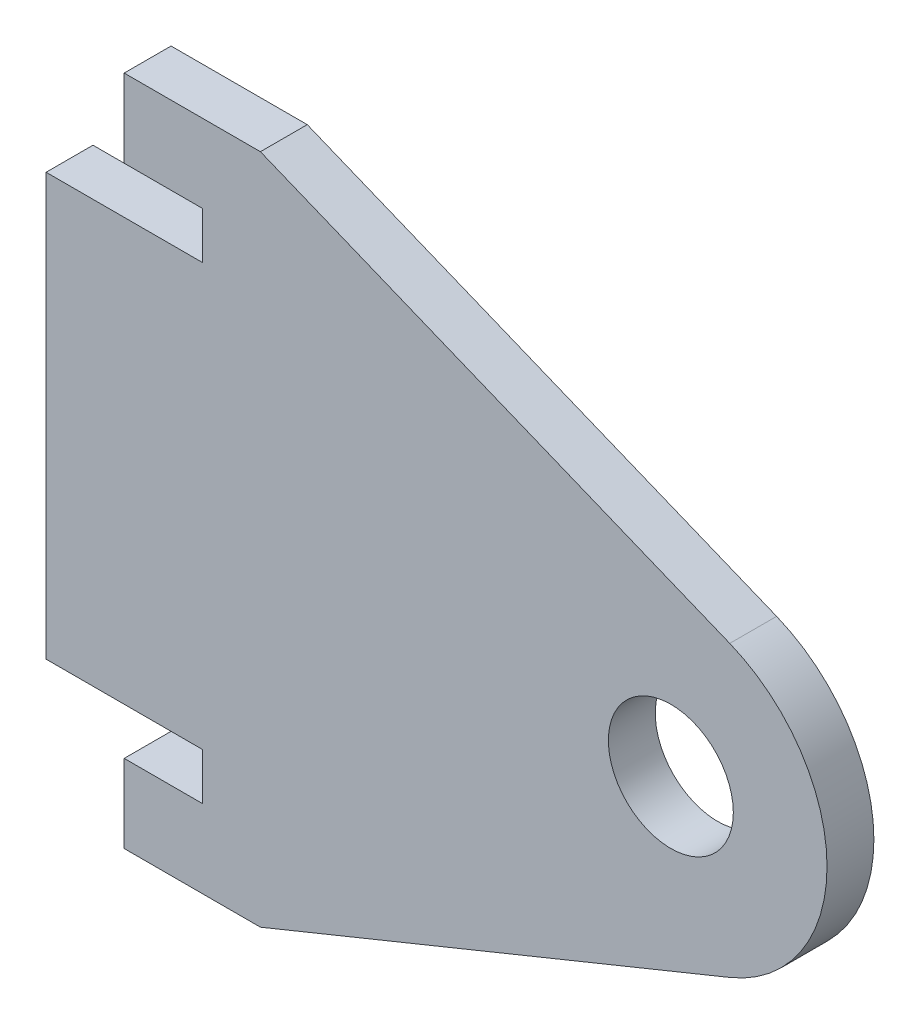
SolidWorks part; units mm, degrees
ref_plane "Plan de face" through (0, 0, 0) normal (0, 0, 1) x (1, 0, 0)
ref_plane "Plan de dessus" through (0, 0, 0) normal (0, 1, 0) x (1, 0, 0)
ref_plane "Plan de droite" through (0, 0, 0) normal (1, 0, 0) x (0, 0, -1)
sketch "Esquisse1" plane through (0, 0, 0) normal (0, 0, 1) x (1, 0, 0)
  line L0 (-11.6615, 23.4846) -> (-11.6615, -3.5154)
  line L1 (-11.6615, 31.4846) -> (2.0593, 31.4846)
  line L2 (-11.6615, 31.4846) -> (-11.6615, 26.4846)
  line L3 (-11.6615, -11.5154) -> (2.0593, -11.5154)
  line L5 (-11.6615, 26.4846) -> (-1.6615, 26.4846)
  line L7 (-11.6615, 23.4846) -> (-1.6615, 23.4846)
  line L8 (-1.6615, 26.4846) -> (-1.6615, 23.4846)
  line L9 (-11.6615, -3.5154) -> (-1.6615, -3.5154)
  line L11 (-11.6615, -6.5154) -> (-1.6615, -6.5154)
  line L12 (-1.6615, -3.5154) -> (-1.6615, -6.5154)
  line L13 (-11.6615, -6.5154) -> (-11.6615, -11.5154)
  line L14 (-11.6615, 9.9846) -> (28.3385, 9.9846) construction
  line L15 (2.0593, 31.4846) -> (32.1103, 19.246)
  line L16 (32.1103, 0.7232) -> (2.0593, -11.5154)
  circle A0 centre (28.3385, 9.9846) radius 4
  arc A1 (32.1103, 19.246) -> (32.1103, 0.7232) centre (28.3385, 9.9846) cw
  dimension "D6" = 8
  dimension "D7" = 10
  dimension "D1" = 3
  dimension "D2" = 3
  dimension "D3" = 33
  dimension "D4" = 5
  dimension "D5" = 5
  dimension "D8" = 10
  dimension "D9" = 10
  dimension "D10" = 40
extrude "Boss.-Extru.1" add sketch "Esquisse1" along normal blind 3
sketch "Esquisse2" plane through (0, 0, 3) normal (0, 0, 1) x (1, 0, 0)
  line L0 (-11.6615, 31.4846) -> (-11.6615, 26.4846) construction
  line L1 (-12.5217, 35.1219) -> (-6.6615, 35.1219)
  line L2 (-12.5217, 35.1219) -> (-12.5217, 25.0874)
  line L3 (-12.5217, 25.0874) -> (-6.6615, 25.0874)
  line L4 (-6.6615, 35.1219) -> (-6.6615, 25.0874)
  line L5 (-11.6615, 9.9846) -> (6.3373, 9.9846) construction
  line L6 (-11.6615, 23.4846) -> (-11.6615, -3.5154) construction
  line L7 (-12.5217, -5.1181) -> (-6.6615, -5.1181)
  line L8 (-6.6615, -15.1526) -> (-6.6615, -5.1181)
  line L9 (-12.5217, -15.1526) -> (-6.6615, -15.1526)
  line L10 (-12.5217, -15.1526) -> (-12.5217, -5.1181)
  dimension "D1" = 5
extrude "Enlèv. mat.-Extru.1" cut sketch "Esquisse2" against normal up to next
